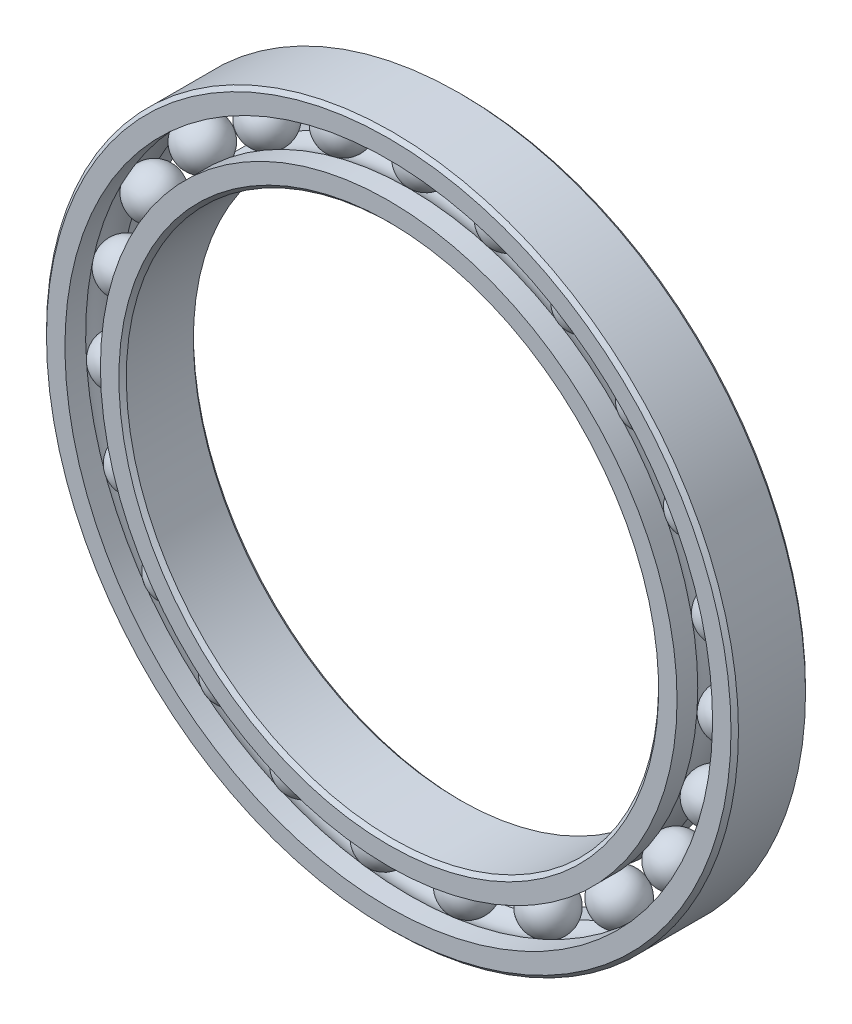
SolidWorks part; units mm, degrees
ref_plane "Front Plane" through (0, 0, 0) normal (0, 0, 1) x (1, 0, 0)
ref_plane "Top Plane" through (0, 0, 0) normal (0, 1, 0) x (1, 0, 0)
ref_plane "Right Plane" through (0, 0, 0) normal (1, 0, 0) x (0, 0, -1)
sketch "Sketch1" plane through (0, 0, 0) normal (0, 0, 1) x (1, 0, 0)
  circle A0 centre (0, 0) radius 32.5
  circle A1 centre (0, 0) radius 25
  dimension "OD" = 65
  dimension "ID" = 50
  dimension "For Shaft Diameter" = 50
  dimension "For Housing ID" = 65
sketch "Sketch5" plane through (0, 0, 0) normal (1, 0, 0) x (0, 0, -1)
  line L0 (-3.5, 0) -> (3.5, 0) construction
  line L1 (0, 32.5) -> (0, -32.5) construction
  line L2 (3.15, 32.5) -> (-3.15, 32.5)
  line L3 (-3.15, 32.5) -> (-3.5, 32.15)
  line L4 (-3.5, 32.15) -> (-3.5, 30.4167)
  line L5 (-3.5, 30.4167) -> (-1.5556, 30.4167)
  line L6 (3.5, 30.4167) -> (1.5556, 30.4167)
  line L7 (3.5, 32.15) -> (3.5, 30.4167)
  line L8 (3.15, 32.5) -> (3.5, 32.15)
  line L9 (0, 32.5) -> (0, 28.75) construction
  line L10 (0, 28.75) -> (0, 25) construction
  line L11 (-2.2798, 28.75) -> (-3.5, 28.75) construction
  line L12 (2.6994, 27.1087) -> (3.0804, 27.1087) construction
  line L13 (-2.6994, 27.1087) -> (-3.0804, 27.1087) construction
  line L14 (-2.6994, 27.1087) -> (-2.6994, 30.3913) construction
  line L15 (-2.6994, 30.3913) -> (-3.0804, 30.3913) construction
  line L16 (-3.0804, 27.1087) -> (-3.0804, 30.3913) construction
  line L17 (-2.6994, 27.1087) -> (-3.0804, 30.3913) construction
  line L18 (-2.6994, 30.3913) -> (-3.0804, 27.1087) construction
  line L19 (3.0804, 27.1087) -> (3.0804, 30.3913) construction
  line L20 (2.6994, 30.3913) -> (3.0804, 30.3913) construction
  line L21 (2.6994, 27.1087) -> (2.6994, 30.3913) construction
  line L22 (0, 32.5) -> (0, -32.5) construction
  arc A0 (-1.5556, 30.4167) -> (1.5556, 30.4167) centre (0, 28.75) cw
  circle A1 centre (0, 28.75) radius 2.2798 construction
  point P14 (0, 25)
  point P15 (-2.8899, 28.75)
  dimension "D1" = 45
  dimension "D2" = 0.35
  dimension "D3" = 3.1111
  dimension "D4" = 1.6667
  dimension "D5" = 0.381
  dimension "D6" = 0.0254
  dimension "Width" = 7
sketch "Sketch6" plane through (0, 0, 0) normal (1, 0, 0) x (0, 0, -1)
  line L0 (3.15, 32.5) -> (3.5, 32.15) construction
  line L1 (3.5, 32.15) -> (3.5, 30.4167) construction
  line L2 (3.5, 30.4167) -> (1.5556, 30.4167) construction
  line L3 (-3.5, 30.4167) -> (-1.5556, 30.4167) construction
  line L4 (-3.5, 32.15) -> (-3.5, 30.4167) construction
  line L5 (-3.15, 32.5) -> (-3.5, 32.15) construction
  line L6 (3.15, 32.5) -> (-3.15, 32.5) construction
  line L7 (3.15, 32.5) -> (3.5, 32.15)
  line L8 (3.5, 32.15) -> (3.5, 30.4167)
  line L9 (3.5, 30.4167) -> (1.5556, 30.4167)
  line L10 (-3.5, 30.4167) -> (-1.5556, 30.4167)
  line L11 (-3.5, 32.15) -> (-3.5, 30.4167)
  line L12 (-3.15, 32.5) -> (-3.5, 32.15)
  line L13 (3.15, 32.5) -> (-3.15, 32.5)
  arc A0 (1.5556, 30.4167) -> (-1.5556, 30.4167) centre (0, 28.75) ccw construction
  arc A1 (1.5556, 30.4167) -> (-1.5556, 30.4167) centre (0, 28.75) ccw
revolve "Revolve5" add sketch "Sketch6" angle 360 about L0
sketch "Sketch3" plane through (0, 0, 0) normal (1, 0, 0) x (0, 0, -1)
  line L0 (-3.5, 27.0833) -> (-1.5556, 27.0833)
  line L1 (0, 32.5) -> (0, -32.5) construction
  line L2 (-3.5, 32.15) -> (-3.5, 30.4167) construction
  line L3 (-3.5, 27.0833) -> (-3.5, 25.35)
  line L4 (-3.15, 32.5) -> (-3.5, 32.15) construction
  line L5 (-3.5, 25.35) -> (-3.15, 25)
  line L6 (-3.15, 25) -> (3.15, 25)
  line L8 (3.15, 25) -> (3.5, 25.35)
  line L10 (3.5, 25.35) -> (3.5, 27.0833)
  line L11 (3.5, 27.0833) -> (1.5556, 27.0833)
  line L12 (3.15, 32.5) -> (3.15, -32.5) construction
  line L13 (3.15, 32.5) -> (3.5, 32.15) construction
  line L14 (3.5, -32.15) -> (3.5, 32.15) construction
  arc A0 (1.5556, 30.4167) -> (-1.5556, 30.4167) centre (0, 28.75) ccw construction
  arc A1 (1.5556, 27.0833) -> (-1.5556, 27.0833) centre (0, 28.75) cw
revolve "Revolve3" add sketch "Sketch3" angle 360 about L0
sketch "Sketch4" plane through (0, 0, 0) normal (1, 0, 0) x (0, 0, -1)
  line L0 (-2.2798, 28.75) -> (2.2798, 28.75)
  arc A2 (-2.2798, 28.75) -> (2.2798, 28.75) centre (0, 28.75) cw
  arc A3 (1.5556, 30.4167) -> (-1.5556, 30.4167) centre (0, 28.75) ccw construction
revolve "Revolve4" add sketch "Sketch4" angle 360 about L0
pattern_circular "CirPattern1" count 23 over 360 about axis through (0, 0, 0) along (0, 0, 1) of bodies 104
equation "\"D2@Sketch5\" = \"Width@Sketch5\" * .05"
equation "\"D3@Sketch5\" = \"Width@Sketch5\" / 2.25"
equation "\"D4@Sketch5\"=((\"OD@Sketch1\"-\"ID@Sketch1\")/2)/4.5"
